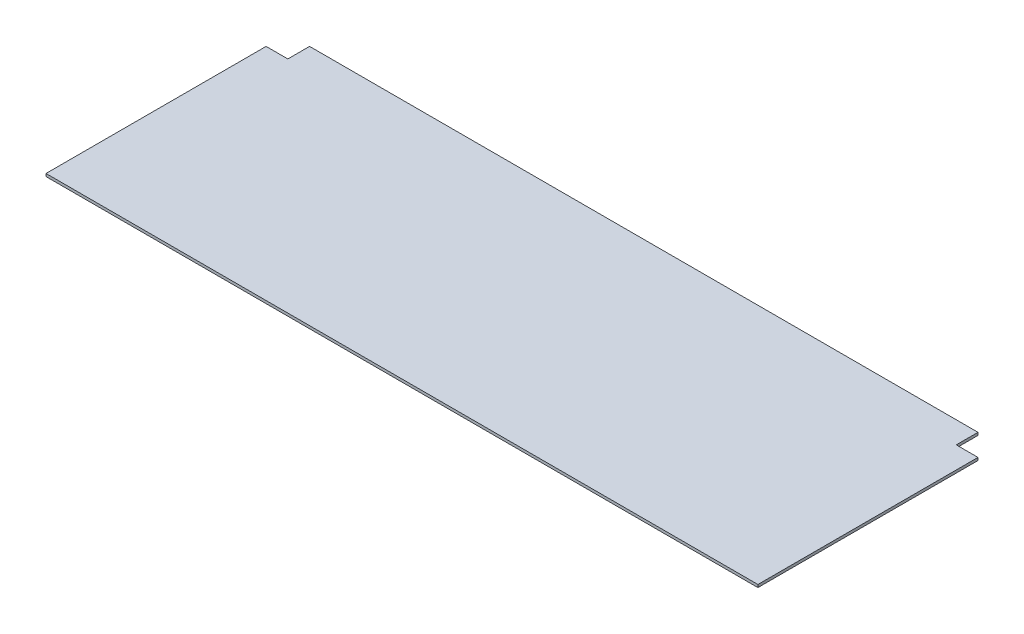
SolidWorks part; units mm, degrees
ref_plane "Front Plane" through (0, 0, 0) normal (0, 0, 1) x (1, 0, 0)
ref_plane "Top Plane" through (0, 0, 0) normal (0, 1, 0) x (1, 0, 0)
ref_plane "Right Plane" through (0, 0, 0) normal (1, 0, 0) x (0, 0, -1)
sketch "Sketch1" plane through (0, 0, 0) normal (0, 1, 0) x (1, 0, 0)
  line L1 (-831.85, -282.575) -> (831.85, -282.575)
  line L2 (-831.85, -282.575) -> (-831.85, 282.575)
  line L3 (-831.85, 282.575) -> (831.85, 282.575)
  line L4 (831.85, -282.575) -> (831.85, 282.575)
  line L5 (-831.85, -282.575) -> (831.85, 282.575) construction
  line L6 (-831.85, 282.575) -> (831.85, -282.575) construction
  line L7 (831.85, 282.575) -> (781.05, 282.575)
  line L8 (831.85, 282.575) -> (831.85, 231.775)
  line L9 (831.85, 231.775) -> (781.05, 231.775)
  line L10 (781.05, 282.575) -> (781.05, 231.775)
  line L11 (-831.85, 282.575) -> (-781.05, 282.575)
  line L12 (-831.85, 282.575) -> (-831.85, 231.775)
  line L13 (-831.85, 231.775) -> (-781.05, 231.775)
  line L14 (-781.05, 282.575) -> (-781.05, 231.775)
  point P0 (0, 0)
  dimension "D1" = 1663.7
  dimension "D2" = 565.15
  dimension "D3" = 50.8
  dimension "D4" = 50.8
  dimension "D5" = 50.8
  dimension "D6" = 50.8
extrude "Boss-Extrude1" add sketch "Sketch1" along normal blind 6.35 contours L3 L14 L13 L2 L1 L4 L9 L10
